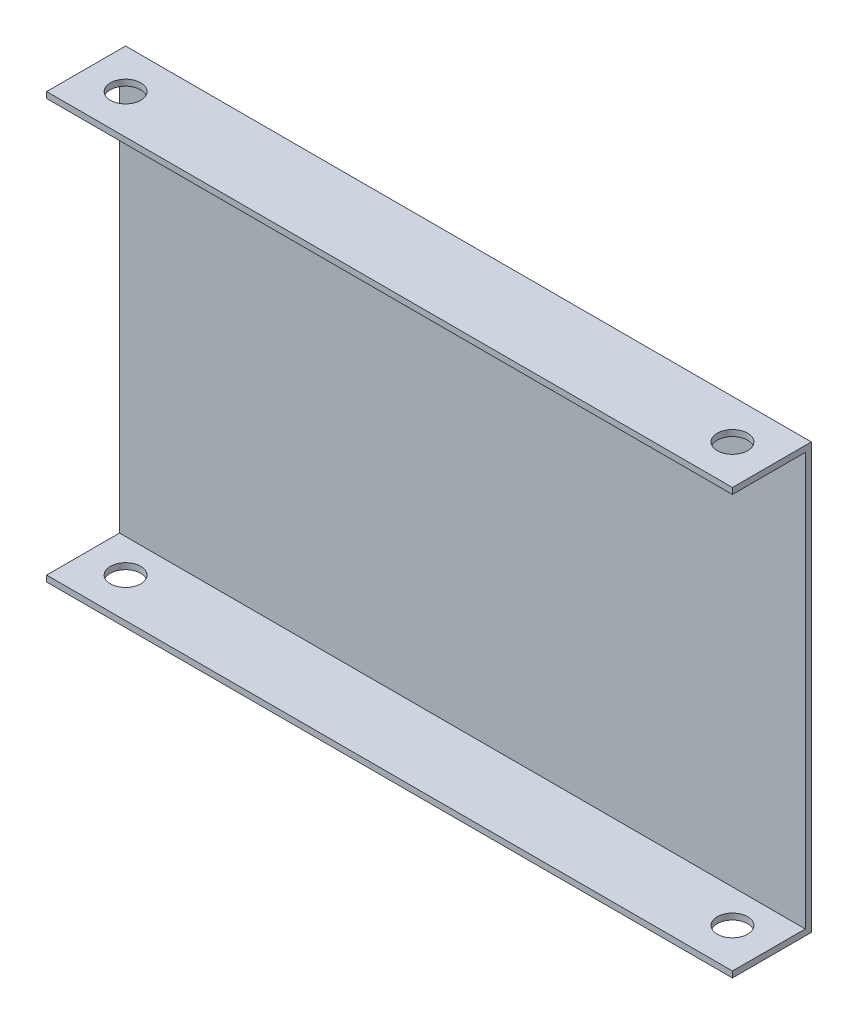
SolidWorks part; units mm, degrees
material "Plain Carbon Steel"
ref_plane "Front Plane" through (0, 0, 0) normal (0, 0, 1) x (1, 0, 0)
ref_plane "Top Plane" through (0, 0, 0) normal (0, 1, 0) x (1, 0, 0)
ref_plane "Right Plane" through (0, 0, 0) normal (1, 0, 0) x (0, 0, -1)
sketch "Sketch3" plane through (0, 0, 0) normal (0, 0, 1) x (1, 0, 0)
  line L1 (-143.51, -88.9) -> (143.51, -88.9)
  line L2 (-143.51, -88.9) -> (-143.51, 88.9)
  line L3 (-143.51, 88.9) -> (143.51, 88.9)
  line L4 (143.51, -88.9) -> (143.51, 88.9)
  line L5 (-143.51, -88.9) -> (143.51, 88.9) construction
  line L6 (-143.51, 88.9) -> (143.51, -88.9) construction
  point P0 (0, 0)
  dimension "D1" = 287.02
  dimension "D2" = 177.8
extrude "Boss-Extrude1" add sketch "Sketch3" along normal blind 33.02
sketch "Sketch4" plane through (0, 0, 33.02) normal (0, 0, 1) x (1, 0, 0)
  line L8 (140.97, -86.36) -> (140.97, 86.36)
  line L9 (140.97, 86.36) -> (-140.97, 86.36)
  line L10 (-140.97, 86.36) -> (-140.97, -86.36)
  line L11 (-140.97, -86.36) -> (140.97, -86.36)
  line L12 (140.97, -86.36) -> (140.97, 86.36)
  line L13 (140.97, 86.36) -> (-140.97, 86.36)
  line L14 (-140.97, 86.36) -> (-140.97, -86.36)
  line L15 (-140.97, -86.36) -> (140.97, -86.36)
  dimension "D1" = 2.54
extrude "Cut-Extrude1" cut sketch "Sketch4" against normal blind 30.48
sketch "Sketch5" plane through (-140.97, 0, 0) normal (1, 0, 0) x (0, 0, -1)
  line L4 (-33.02, 86.36) -> (-33.02, -86.36)
  line L5 (-33.02, -86.36) -> (-2.54, -86.36)
  line L6 (-2.54, -86.36) -> (-2.54, 86.36)
  line L7 (-2.54, 86.36) -> (-33.02, 86.36)
  line L8 (-33.02, 86.36) -> (-33.02, -86.36)
  line L9 (-33.02, -86.36) -> (-2.54, -86.36)
  line L10 (-2.54, -86.36) -> (-2.54, 86.36)
  line L11 (-2.54, 86.36) -> (-33.02, 86.36)
  dimension "D1" = 0
extrude "Cut-Extrude2" cut sketch "Sketch5" against normal through all both and the other way through all
sketch "Sketch6" plane through (0, -86.36, 0) normal (0, 1, 0) x (1, 0, 0)
  line L0 (133.35, -96.52) -> (133.35, 45.72) construction
  line L2 (-143.51, -33.02) -> (143.51, -33.02) construction
  line L3 (143.51, -33.02) -> (143.51, -2.54) construction
  circle A0 centre (127, -16.51) radius 6.35
  circle A1 centre (-127, -16.51) radius 6.35
  dimension "D1" = 12.7
  dimension "D2" = 6.35
  dimension "D3" = 16.51
  dimension "D5" = 270.51
  dimension "D4" = 2
extrude "Cut-Extrude3" cut sketch "Sketch6" against normal through all both and the other way through all
